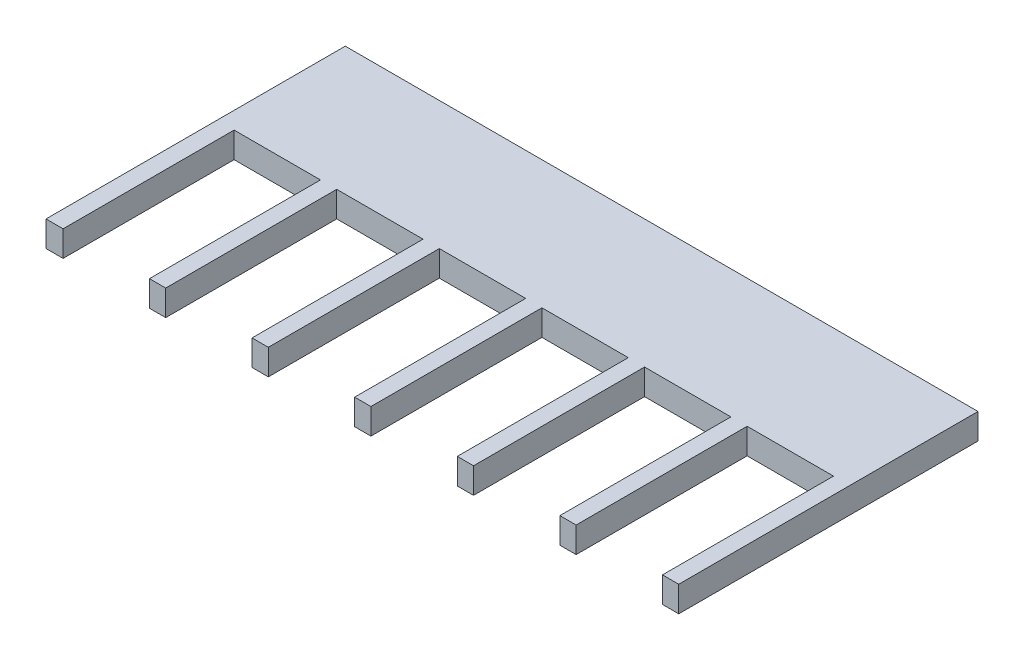
SolidWorks part; units mm, degrees
ref_plane "Front Plane" through (0, 0, 0) normal (0, 0, 1) x (1, 0, 0)
ref_plane "Top Plane" through (0, 0, 0) normal (0, 1, 0) x (1, 0, 0)
ref_plane "Right Plane" through (0, 0, 0) normal (1, 0, 0) x (0, 0, -1)
sketch "Sketch1" plane through (0, 0, 0) normal (0, 1, 0) x (1, 0, 0)
  line L5 (2, -35) -> (2, -15)
  line L7 (12.1, -15) -> (12.1, -35)
  line L30 (0, -35) -> (0, 0)
  line L31 (0, 0) -> (74, 0)
  line L32 (7.05, 0) -> (7.05, -35) construction
  line L33 (14, -35) -> (14, -15)
  line L34 (24.1, -15) -> (24.1, -35)
  line L35 (14, -15) -> (19.05, -15)
  line L36 (24.1, -15) -> (19.05, -15)
  line L37 (19.05, 0) -> (19.05, -35) construction
  line L38 (2, -15) -> (7.05, -15)
  line L39 (12.1, -15) -> (7.05, -15)
  line L40 (26, -35) -> (26, -15)
  line L41 (36.1, -15) -> (36.1, -35)
  line L42 (26, -15) -> (31.05, -15)
  line L43 (36.1, -15) -> (31.05, -15)
  line L44 (31.05, 0) -> (31.05, -35) construction
  line L45 (38, -35) -> (38, -15)
  line L46 (48.1, -15) -> (48.1, -35)
  line L47 (38, -15) -> (43.05, -15)
  line L48 (48.1, -15) -> (43.05, -15)
  line L49 (43.05, 0) -> (43.05, -35) construction
  line L50 (50, -35) -> (50, -15)
  line L51 (60.1, -15) -> (60.1, -35)
  line L52 (50, -15) -> (55.05, -15)
  line L53 (60.1, -15) -> (55.05, -15)
  line L54 (55.05, 0) -> (55.05, -35) construction
  line L55 (62, -35) -> (62, -15)
  line L56 (72.1, -15) -> (72.1, -35)
  line L57 (62, -15) -> (67.05, -15)
  line L58 (72.1, -15) -> (67.05, -15)
  line L59 (67.05, 0) -> (67.05, -35) construction
  line L60 (0, -35) -> (2, -35)
  line L61 (12.1, -35) -> (14, -35)
  line L62 (24.1, -35) -> (26, -35)
  line L63 (36.1, -35) -> (38, -35)
  line L64 (48.1, -35) -> (50, -35)
  line L65 (60.1, -35) -> (62, -35)
  line L66 (72.1, -35) -> (74, -35)
  line L67 (74, -35) -> (74, 0)
  dimension "D1" = 35
  dimension "D2" = 10.1
  dimension "D4" = 20
extrude "Boss-Extrude1" add sketch "Sketch1" along normal blind 3
